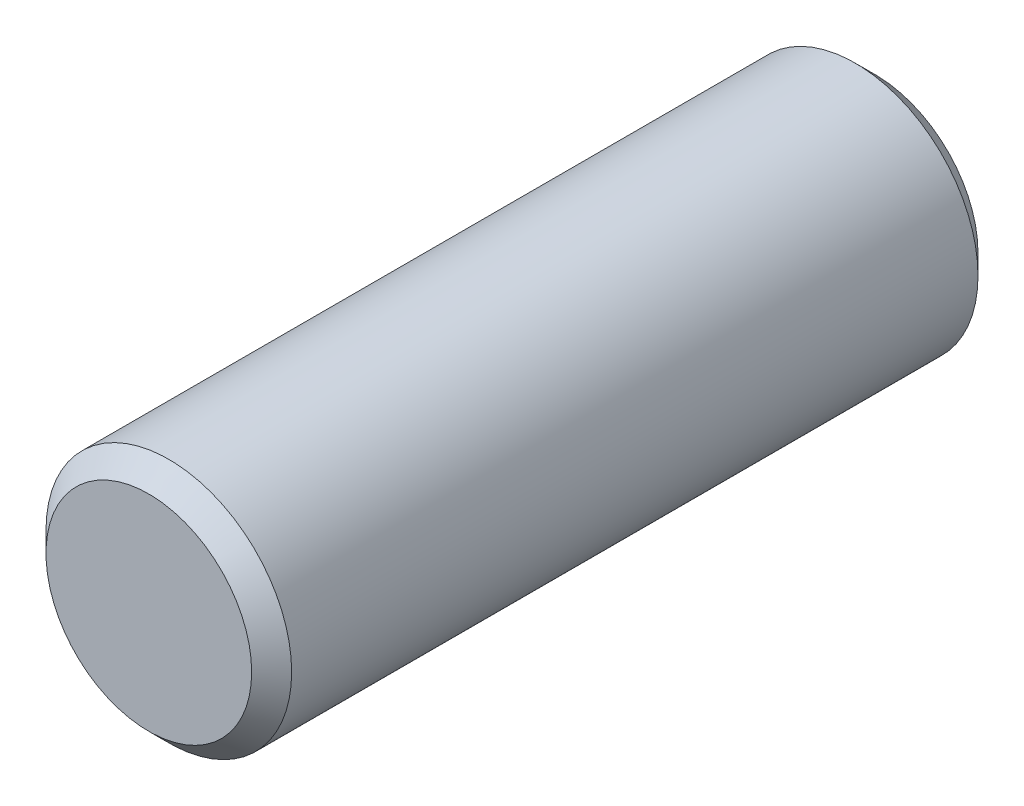
SolidWorks part; units mm, degrees
ref_plane "Front Plane" through (0, 0, 0) normal (0, 0, 1) x (1, 0, 0)
ref_plane "Top Plane" through (0, 0, 0) normal (0, 1, 0) x (1, 0, 0)
ref_plane "Right Plane" through (0, 0, 0) normal (1, 0, 0) x (0, 0, -1)
sketch "Sketch1" plane through (0, 0, 0) normal (0, 0, 1) x (1, 0, 0)
  circle A0 centre (0, 0) radius 3.12
  dimension "D1" = 6.24
extrude "Extrude1" add sketch "Sketch1" along normal blind 18.45
chamfer "Chamfer1" distance 0.508 angle 45 2 edges at (3.12, 0, 0) (3.12, 0, 18.45)
